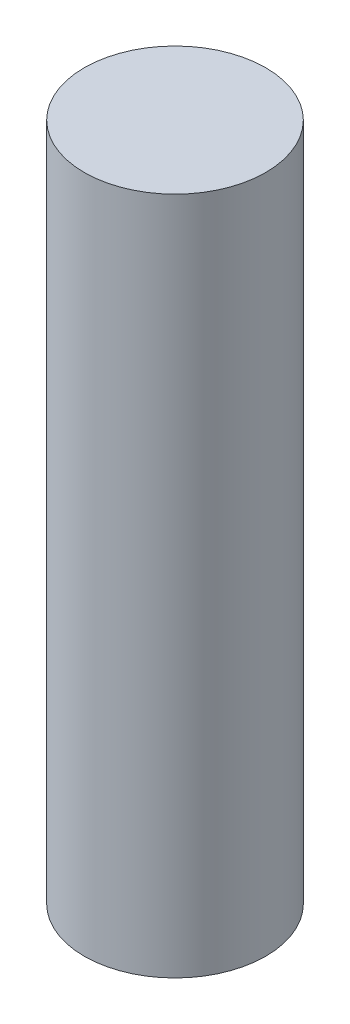
SolidWorks part; units mm, degrees
ref_plane "Front Plane" through (0, 0, 0) normal (0, 0, 1) x (1, 0, 0)
ref_plane "Top Plane" through (0, 0, 0) normal (0, 1, 0) x (1, 0, 0)
ref_plane "Right Plane" through (0, 0, 0) normal (1, 0, 0) x (0, 0, -1)
sketch "Sketch2" plane through (0, 0, 0) normal (0, 1, 0) x (1, 0, 0)
  circle A0 centre (0, 0) radius 1
  dimension "D1" = 2
extrude "Boss-Extrude1" add sketch "Sketch2" along normal blind 7.48
